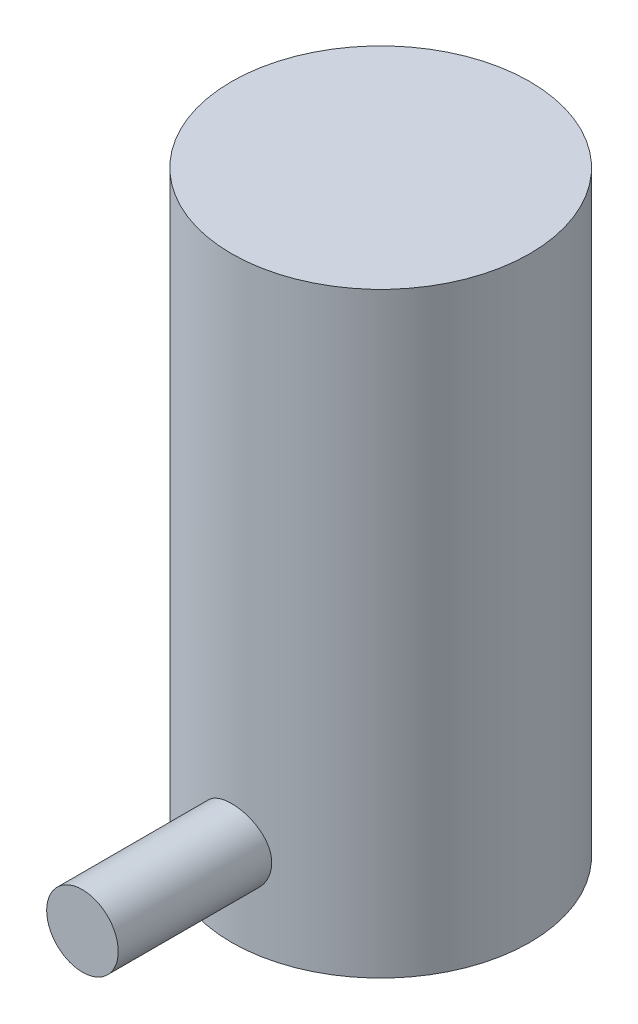
SolidWorks part; units mm, degrees
ref_plane "Front Plane" through (0, 0, 0) normal (0, 0, 1) x (1, 0, 0)
ref_plane "Top Plane" through (0, 0, 0) normal (0, 1, 0) x (1, 0, 0)
ref_plane "Right Plane" through (0, 0, 0) normal (1, 0, 0) x (0, 0, -1)
sketch "Sketch1" plane through (0, 0, 0) normal (0, 1, 0) x (1, 0, 0)
  circle A0 centre (0, 0) radius 6.35
  dimension "D1" = 12.7
extrude "Boss-Extrude1" add sketch "Sketch1" along normal blind 25.4 contours A0
sketch "Sketch2" plane through (0, 0, 0) normal (0, 0, 1) x (1, 0, 0)
  line L0 (0, 25.4) -> (0, 0) construction
  line L1 (6.35, 25.4) -> (-6.35, 25.4) construction
  circle A0 centre (0, 3.6) radius 1.524
  dimension "D1" = 3.048
extrude "Boss-Extrude2" add sketch "Sketch2" along normal blind 12.7 contours A0
